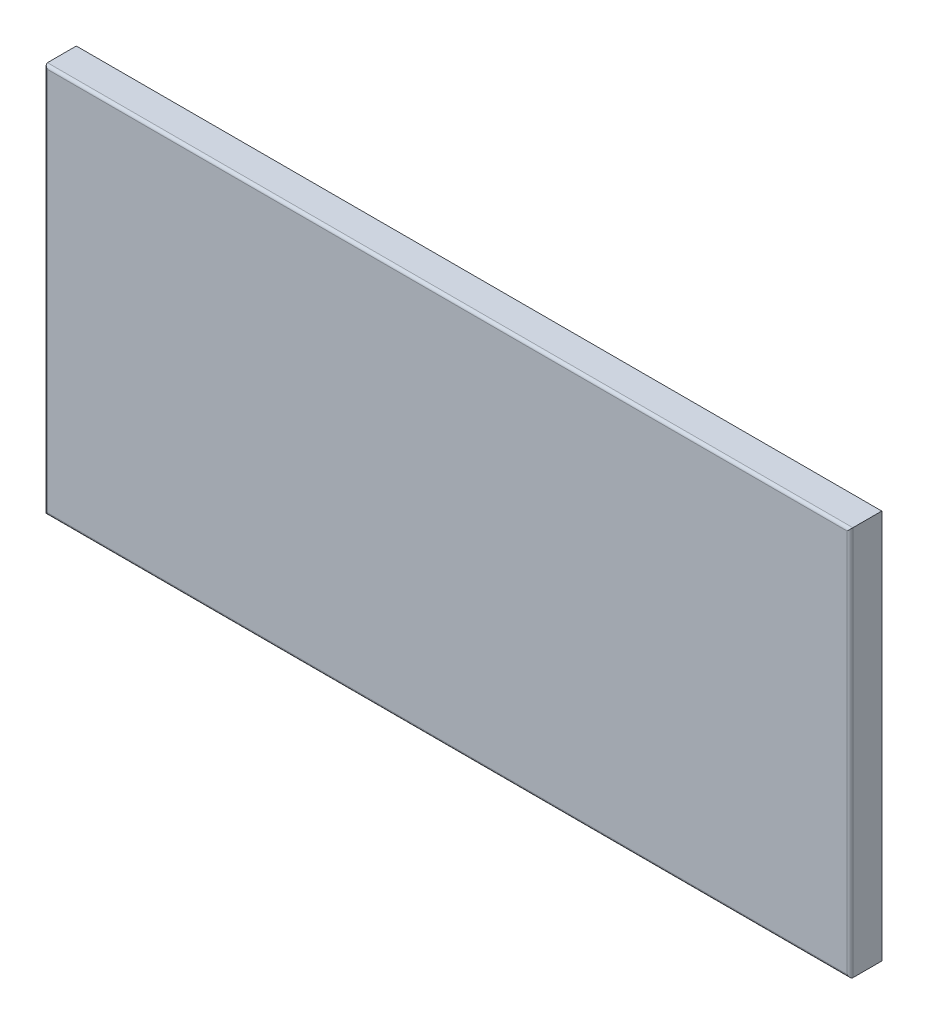
SolidWorks part; units mm, degrees
material "ABS PC"
ref_plane "Plan de face" through (0, 0, 0) normal (0, 0, 1) x (1, 0, 0)
ref_plane "Plan de dessus" through (0, 0, 0) normal (0, 1, 0) x (1, 0, 0)
ref_plane "Plan de droite" through (0, 0, 0) normal (1, 0, 0) x (0, 0, -1)
sketch "Esquisse1" plane through (0, 0, 0) normal (0, 0, 1) x (1, 0, 0)
  line L1 (0, 0) -> (27.9, 0)
  line L2 (0, 0) -> (0, 13.5)
  line L3 (0, 13.5) -> (27.9, 13.5)
  line L4 (27.9, 0) -> (27.9, 13.5)
  dimension "D1" = 27.9
  dimension "D2" = 13.5
extrude "Boss.-Extru.1" add sketch "Esquisse1" along normal blind 1.1
fillet "Congé1" radius 0.1 4 edges at (27.9, 6.75, 1.1) (13.95, 13.5, 1.1) (0, 6.75, 1.1) (13.95, 0, 1.1)
